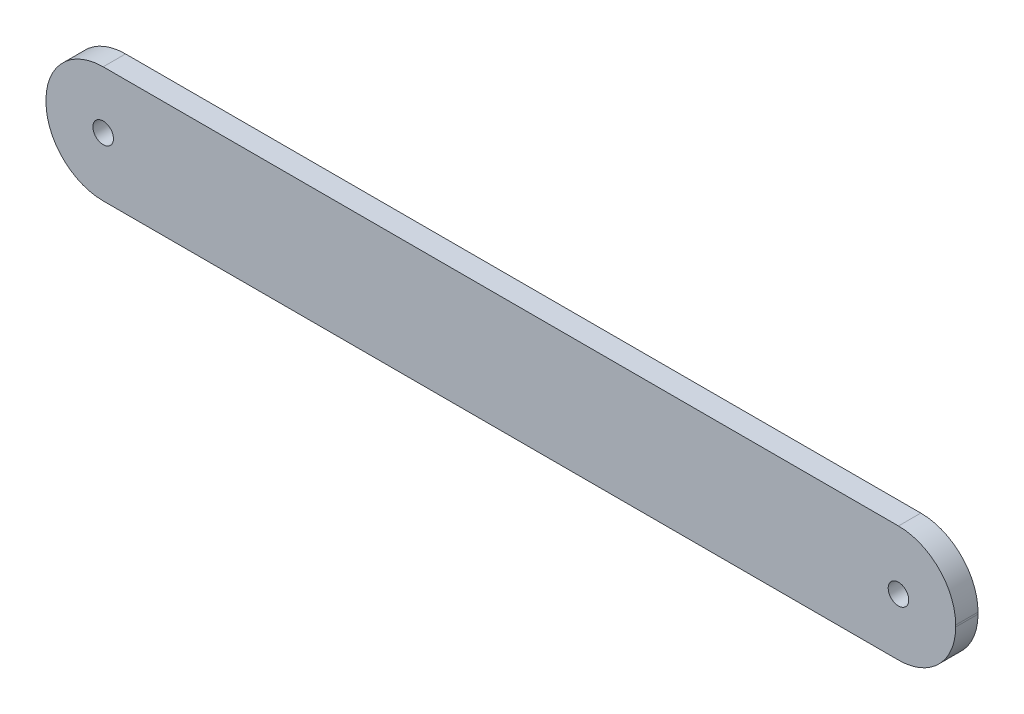
SolidWorks part; units mm, degrees
material "Acrylic (Medium-high impact)"
ref_plane "Front Plane" through (0, 0, 0) normal (0, 0, 1) x (1, 0, 0)
ref_plane "Top Plane" through (0, 0, 0) normal (0, 1, 0) x (1, 0, 0)
ref_plane "Right Plane" through (0, 0, 0) normal (1, 0, 0) x (0, 0, -1)
sketch "Sketch1" plane through (0, 0, 0) normal (0, 0, 1) x (1, 0, 0)
  line L1 (-64.643, -8.255) -> (64.643, -8.255)
  line L2 (-64.643, -8.255) -> (-64.643, 8.255)
  line L3 (-64.643, 8.255) -> (64.643, 8.255)
  line L4 (64.643, -8.255) -> (64.643, 8.255)
  line L5 (-64.643, -8.255) -> (64.643, 8.255) construction
  line L6 (-64.643, 8.255) -> (64.643, -8.255) construction
  point P0 (0, 0)
  dimension "D1" = 129.286
  dimension "D2" = 16.51
extrude "Boss-Extrude1" add sketch "Sketch1" along normal blind 3.175
fillet "Fillet1" radius 8.128 4 edges at (-64.643, -8.255, 1.5875) (-64.643, 8.255, 1.5875) (64.643, -8.255, 1.5875) (64.643, 8.255, 1.5875)
sketch "Sketch2" plane through (0, 0, 3.175) normal (0, 0, 1) x (1, 0, 0)
  circle A0 centre (-56.515, 0.127) radius 1.4605
  circle A1 centre (56.515, -0.127) radius 1.4605
  dimension "D1" = 2.921
  dimension "D2" = 2.921
extrude "Cut-Extrude1" cut sketch "Sketch2" against normal through all
